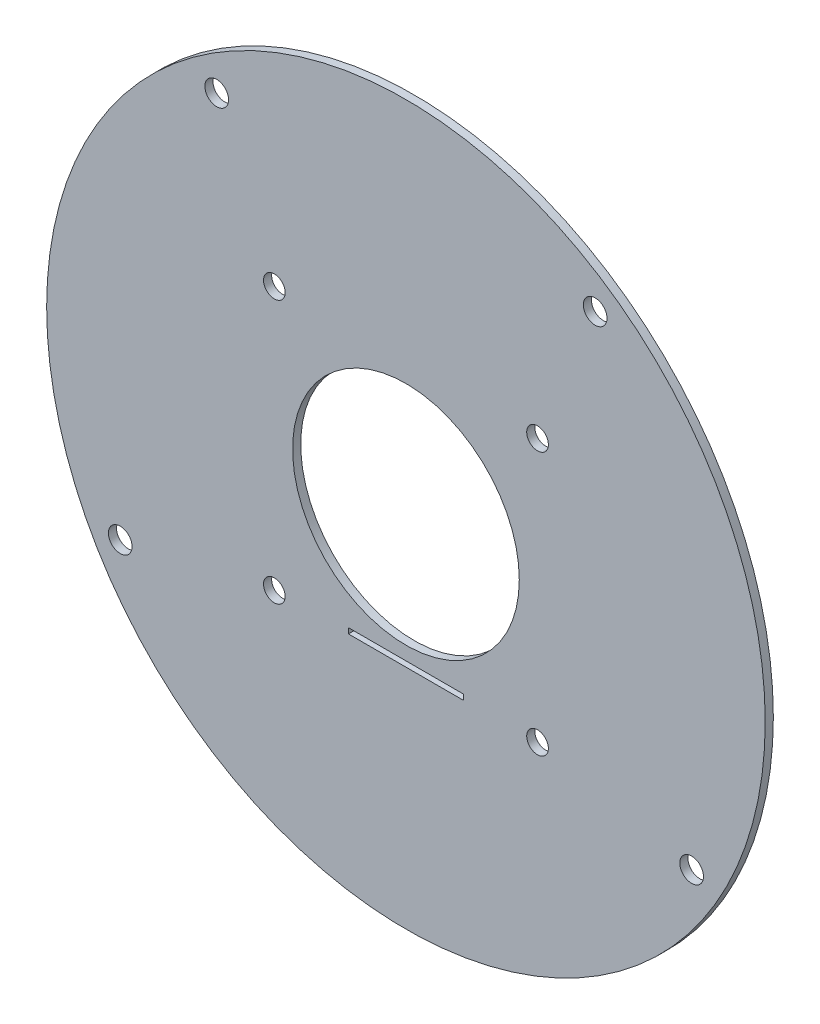
SolidWorks part; units mm, degrees
material "E-Glass Fiber"
ref_plane "Front Plane" through (0, 0, 0) normal (0, 0, 1) x (1, 0, 0)
ref_plane "Top Plane" through (0, 0, 0) normal (0, 1, 0) x (1, 0, 0)
ref_plane "Right Plane" through (0, 0, 0) normal (1, 0, 0) x (0, 0, -1)
sketch "Sketch8" plane through (0, 0, 0) normal (0, 0, 1) x (1, 0, 0)
  line L4 (-10.3, -6.3) -> (10.3, -6.3)
  line L5 (10.3, -6.3) -> (10.3, 8.1)
  line L6 (10.3, 8.1) -> (-10.3, 8.1)
  line L7 (-10.3, 8.1) -> (-10.3, -6.3)
  line L8 (-10.3, -6.3) -> (10.3, -6.3)
  line L9 (10.3, -6.3) -> (10.3, 8.1)
  line L10 (10.3, 8.1) -> (-10.3, 8.1)
  line L11 (-10.3, 8.1) -> (-10.3, -6.3)
  line L12 (13.1, -9.1) -> (13.1, 10.9)
  line L13 (13.1, 10.9) -> (-13.1, 10.9)
  line L14 (-13.1, 10.9) -> (-13.1, -9.1)
  line L15 (-13.1, -9.1) -> (13.1, -9.1)
  line L16 (13.1, -9.1) -> (13.1, 10.9)
  line L17 (13.1, 10.9) -> (-13.1, 10.9)
  line L18 (-13.1, 10.9) -> (-13.1, -9.1)
  line L19 (-13.1, -9.1) -> (13.1, -9.1)
  line L20 (-10.5, 8.3) -> (-10.5, -6.5)
  line L21 (-10.5, -6.5) -> (10.5, -6.5)
  line L22 (10.5, -6.5) -> (10.5, 8.3)
  line L23 (10.5, 8.3) -> (-10.5, 8.3)
  line L24 (-10.5, 8.3) -> (-10.5, -6.5)
  line L25 (-10.5, -6.5) -> (10.5, -6.5)
  line L26 (10.5, -6.5) -> (10.5, 8.3)
  line L27 (10.5, 8.3) -> (-10.5, 8.3)
  line L28 (8.5, 5.3) -> (8.5, 6.3)
  line L29 (-8.5, 5.3) -> (8.5, 5.3)
  line L30 (-8.5, 6.3) -> (-8.5, 5.3)
  line L31 (8.5, 6.3) -> (-8.5, 6.3)
  line L32 (8.5, 5.3) -> (8.5, 6.3)
  line L33 (-8.5, 5.3) -> (8.5, 5.3)
  line L34 (-8.5, 6.3) -> (-8.5, 5.3)
  line L35 (8.5, 6.3) -> (-8.5, 6.3)
  dimension "D1" = 0
  dimension "D2" = 0
  dimension "D3" = 0
  dimension "D4" = 0
sketch "Base" plane through (0, 0, 0) normal (0, 0, 1) x (1, 0, 0)
  line L0 (-53.092, 0) -> (53.092, 0) construction
  line L1 (0, -53.092) -> (0, 53.092) construction
  line L2 (-30, -41.85) -> (30, -41.85)
  line L3 (0, -16.7505) -> (-48.6913, -16.7505) construction
  line L4 (-30.5099, -43.45) -> (30.5099, -43.45)
  line L5 (0, 0) -> (-13.1, -9.1) construction
  line L6 (-13.1, -9.1) -> (-13.2643, -9.2141) construction
  circle A0 centre (0, 0) radius 16.1505
  arc A1 (30.5099, -43.45) -> (-30.5099, -43.45) centre (0, 0) ccw
  circle A3 centre (0, 0) radius 16.7505
  arc A4 (30, -41.85) -> (-30, -41.85) centre (0, 0) ccw
  point P7 (0, 0)
  point P10 (0, 0)
  dimension "D1" = 0.2
  dimension "D2" = 0.6
  dimension "D3" = 53.092
  dimension "D4" = 51.492
  dimension "D6" = 30.5099
  dimension "D5" = 30
sketch "Sketch3" plane through (0, 0, 0) normal (0, 0, 1) x (1, 0, 0)
  line L0 (-30.5099, -43.45) -> (30.5099, -43.45) construction
  line L1 (-30.5099, -43.45) -> (30.5099, -43.45) construction
  line L2 (-16.7505, 0) -> (-16.7505, 50.3803) construction
  line L3 (-16.5395, -50.45) -> (16.5395, -50.45) construction
  line L4 (0, 16.7505) -> (50.3803, 16.7505) construction
  line L5 (16.7505, 0) -> (16.7505, 50.3803) construction
  line L6 (0, -16.7505) -> (-50.3803, -16.7505) construction
  circle A0 centre (0, 0) radius 53.092 construction
  circle A1 centre (0, 0) radius 53.092
  circle A2 centre (0, 0) radius 16.7505 construction
  circle A3 centre (0, 0) radius 16.7505
  dimension "D1" = 7
extrude "PCB" add sketch "Sketch3" along normal blind 1.2
sketch "Sketch5" plane through (0, 0, 1.2) normal (0, 0, 1) x (1, 0, 0)
  line L0 (0, 0) -> (11.8444, -11.8444) construction
  line L1 (11.8444, -11.8444) -> (37.5417, -37.5417) construction
  line L2 (0, 0) -> (-11.8444, 11.8444) construction
  line L3 (-11.8444, 11.8444) -> (-37.5417, 37.5417) construction
  line L18 (0, 0) -> (0, 53.092) construction
  circle A0 centre (19.4454, 19.4454) radius 3.5 construction
  circle A1 centre (-19.4454, -19.4454) radius 1.6
  circle A2 centre (0, 0) radius 16.7505 construction
  circle A3 centre (0, 0) radius 16.7505 construction
  circle A4 centre (-19.4454, 19.4454) radius 3.5 construction
  circle A5 centre (0, 0) radius 53.092 construction
  circle A6 centre (-19.4454, 19.4454) radius 1.6
  circle A7 centre (19.4454, 19.4454) radius 1.6
  circle A8 centre (19.4454, -19.4454) radius 3.5 construction
  circle A9 centre (-19.4454, -19.4454) radius 3.5 construction
  circle A10 centre (19.4454, -19.4454) radius 1.6
  circle A11 centre (0, 0) radius 53.092 construction
  circle A12 centre (0, 0) radius 27.5 construction
  dimension "D1" = 7
  dimension "D2" = 3.2
  dimension "D3" = 55
  dimension "D5" = 45
extrude "Mast" cut sketch "Sketch5" against normal up to next
sketch "Sketch6" plane through (0, 0, 1.2) normal (0, 0, 1) x (1, 0, 0)
  line L0 (0, 0) -> (0, 53.2479) construction
  line L2 (0, 0) -> (-46.114, -26.624) construction
  line L4 (0, 0) -> (46.114, -26.624) construction
  line L6 (0, 0) -> (-53.2479, 0) construction
  line L8 (0, 0) -> (-30.5417, 43.6181) construction
  line L10 (0, 0) -> (30.5417, 43.6181) construction
  circle A2 centre (42.2169, -24.374) radius 4.5 construction
  circle A3 centre (27.9606, 39.9319) radius 4.5 construction
  circle A4 centre (-42.2169, -24.374) radius 4.5 construction
  circle A5 centre (-27.9606, 39.9319) radius 4.5 construction
  circle A6 centre (27.9606, 39.9319) radius 1.75
  circle A7 centre (42.2169, -24.374) radius 1.75
  circle A8 centre (-42.2169, -24.374) radius 1.75
  circle A9 centre (-27.9606, 39.9319) radius 1.75
  arc A10 (30.508, -43.6417) -> (-30.508, -43.6417) centre (0, 0) ccw construction
  arc A11 (30.508, -43.6417) -> (-30.508, -43.6417) centre (0, 0) ccw construction
  dimension "D1" = 120
  dimension "D3" = 9
  dimension "D2" = 3.5
  dimension "D4" = 35
extrude "Enclosure screws" cut sketch "Sketch6" against normal up to next
sketch "Sketch9" plane through (0, 0, 0) normal (0, 0, 1) x (1, 0, 0)
  line L0 (-8.5, -18.7505) -> (-8.5, -19.5505)
  line L1 (-8.5, -19.5505) -> (8.5, -19.5505)
  line L2 (8.5, -19.5505) -> (8.5, -18.7505)
  line L3 (8.5, -18.7505) -> (-8.5, -18.7505)
  line L4 (0, -53.092) -> (0, 53.092) construction
  line L5 (0, -53.092) -> (0, 53.092) construction
  line L6 (0, -16.7505) -> (-48.6913, -16.7505) construction
  dimension "D1" = 0.8
  dimension "D2" = 2
  dimension "D3" = 17
extrude "Flex cable" cut sketch "Sketch9" along normal up to next
sketch "Sketch10" plane through (0, 0, 1.2) normal (0, 0, 1) x (1, 0, 0)
  circle A0 centre (0, 0) radius 50.092 construction
  circle A1 centre (0, 0) radius 53.092 construction
  dimension "D1" = 3
